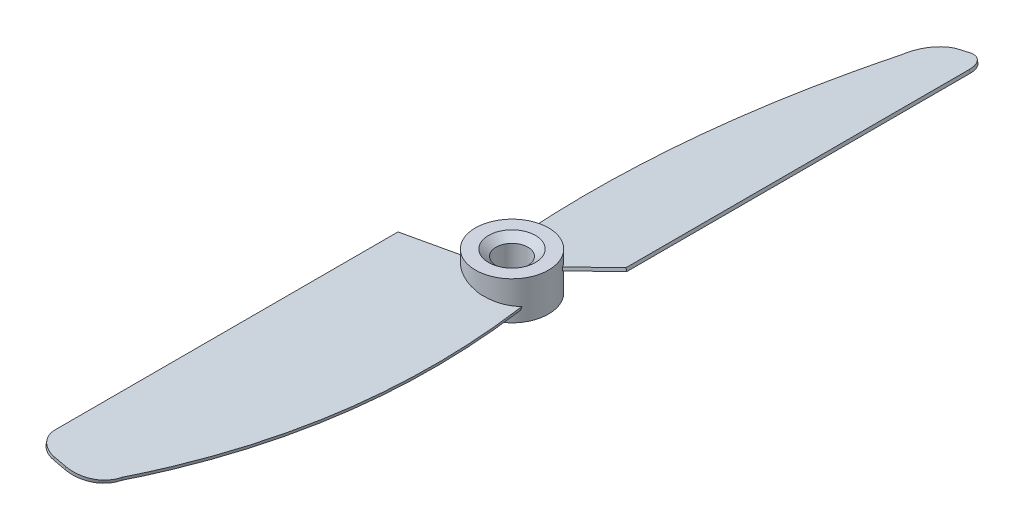
SolidWorks part; units mm, degrees
ref_plane "Front Plane" through (0, 0, 0) normal (0, 0, 1) x (1, 0, 0)
ref_plane "Top Plane" through (0, 0, 0) normal (0, 1, 0) x (1, 0, 0)
ref_plane "Right Plane" through (0, 0, 0) normal (1, 0, 0) x (0, 0, -1)
sketch "Sketch1" plane through (0, 0, 0) normal (0, 1, 0) x (1, 0, 0)
  circle A0 centre (0, 0) radius 5.75
  dimension "D1" = 11.5
extrude "Boss-Extrude1" add sketch "Sketch1" along normal mid plane 6
sketch "Sketch2" plane through (0, 0, 0) normal (0, 0, 1) x (1, 0, 0)
  line L0 (-5.75, 1.3275) -> (5.75, -1.3275) construction
  line L1 (-5.75, 3) -> (-5.75, -3) construction
  line L2 (5.75, -3) -> (5.75, 3) construction
  line L3 (-5.75, -3) -> (5.75, -3) construction
  dimension "D1" = 13
ref_plane "Plane1" through (0, 0, 0) normal (-0.225, -0.9744, 0) x (0.9744, -0.225, 0)
sketch "Sketch3" plane through (0, 0, 0) normal (-0.225, -0.9744, 0) x (0.9744, -0.225, 0)
  line L0 (-4.2179, 2.8014) -> (-11.757, 6.5279)
  line L1 (-11.757, 6.5279) -> (-11.757, 60.5)
  line L2 (-8.757, 63.5) -> (-6.8923, 63.5)
  line L3 (-5.9012, 0) -> (5.9012, 0) construction
  arc A0 (-1.9776, 59.4194) -> (-6.8923, 63.5) centre (-6.8923, 58.5) ccw
  arc A1 (-11.757, 60.5) -> (-8.757, 63.5) centre (-8.757, 60.5) cw
  ellipse E1 centre (-0.6749, 0) end of major axis (-0.6749, 5.75) minor radius 5.6026 construction
  spline S0 degree 2 poles (-4.2179, 2.8014) (1.0705, 9.2258) (4.6584, 1.7614) knots 0 0 0 1 1 1
  spline S1 degree 2 poles (-1.9776, 59.4194) (8.5982, 31.5052) (4.6584, 1.7614) knots 0 0 0 1 1 1
  dimension "D2" = 5
  dimension "D3" = 3
  dimension "D1" = 63.5
extrude "Boss-Extrude2" add sketch "Sketch3" along normal mid plane 0.5
pattern_circular "CirPattern2" count 2 over 360 about axis through (0, 3, 0) along (0, -1, 0) of "Boss-Extrude2"
sketch "Sketch5" plane through (0, -3, 0) normal (0, -1, 0) x (1, 0, 0)
  circle A0 centre (0, 0) radius 2.5
  dimension "D1" = 5
extrude "Cut-Extrude2" cut sketch "Sketch5" against normal through all
chamfer "Chamfer1" distance 1 angle 50 2 edges at (0, -3, -2.5) (0, 3, -2.5)
pattern_circular "CirPattern1" count 2 over 360 about axis through (0, 3, 0) along (0, -1, 0) of "Boss-Extrude2"
sketch "Sketch4" plane through (0, -3, 0) normal (0, -1, 0) x (1, 0, 0)
